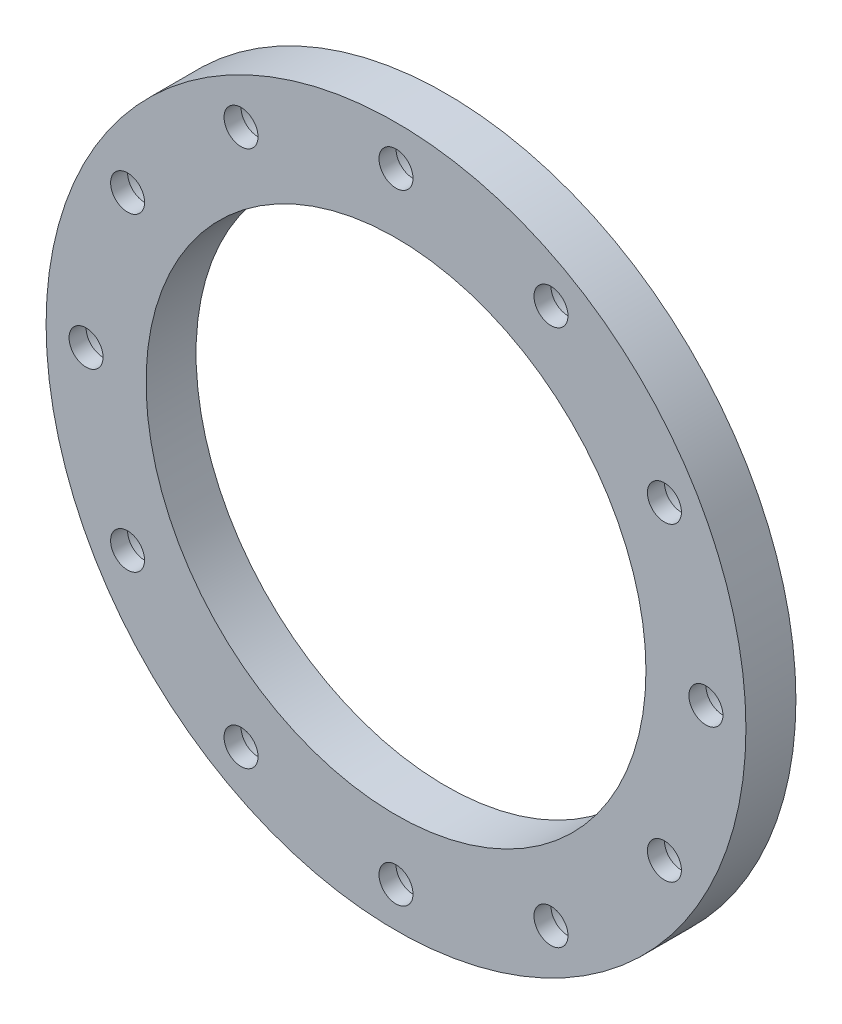
SolidWorks part; units mm, degrees
material "Plain Carbon Steel"
ref_plane "Front Plane" through (0, 0, 0) normal (0, 0, 1) x (1, 0, 0)
ref_plane "Top Plane" through (0, 0, 0) normal (0, 1, 0) x (1, 0, 0)
ref_plane "Right Plane" through (0, 0, 0) normal (1, 0, 0) x (0, 0, -1)
sketch "Sketch1" plane through (0, 0, 0) normal (0, 0, 1) x (1, 0, 0)
  line L0 (0, 0) -> (0, -35) construction
  circle A0 centre (0, 0) radius 35
  circle A1 centre (0, 0) radius 25
  dimension "D1" = 70
  dimension "D2" = 50
extrude "Boss-Extrude1" add sketch "Sketch1" along normal blind 5
sketch "Sketch2" plane through (0, 0, 5) normal (0, 0, 1) x (1, 0, 0)
  line L0 (0, 31) -> (0, 0) construction
  circle A0 centre (0, 31) radius 1.7
  circle A1 centre (15.5, 26.8468) radius 1.7
  circle A2 centre (26.8468, 15.5) radius 1.7
  circle A3 centre (31, 0) radius 1.7
  circle A4 centre (26.8468, -15.5) radius 1.7
  circle A5 centre (15.5, -26.8468) radius 1.7
  circle A6 centre (0, -31) radius 1.7
  circle A7 centre (-15.5, -26.8468) radius 1.7
  circle A8 centre (-26.8468, -15.5) radius 1.7
  circle A9 centre (-31, 0) radius 1.7
  circle A10 centre (-26.8468, 15.5) radius 1.7
  circle A11 centre (-15.5, 26.8468) radius 1.7
  point P29 (0, 0)
  dimension "D1" = 3.4
  dimension "D2" = 31
  dimension "D3" = 12
extrude "Cut-Extrude1" cut sketch "Sketch2" against normal up to next
sketch "Sketch3" plane through (0, 0, 0) normal (0, 0, -1) x (-1, 0, 0)
  circle A0 centre (0, 31) radius 3.3
  dimension "D1" = 6.6
extrude "Cut-Extrude2" cut sketch "Sketch3" against normal blind 3.3
pattern_circular "CirPattern1" count 12 over 360 about axis through (0, 0, 0) along (0, 0, 1) of "Cut-Extrude2"
